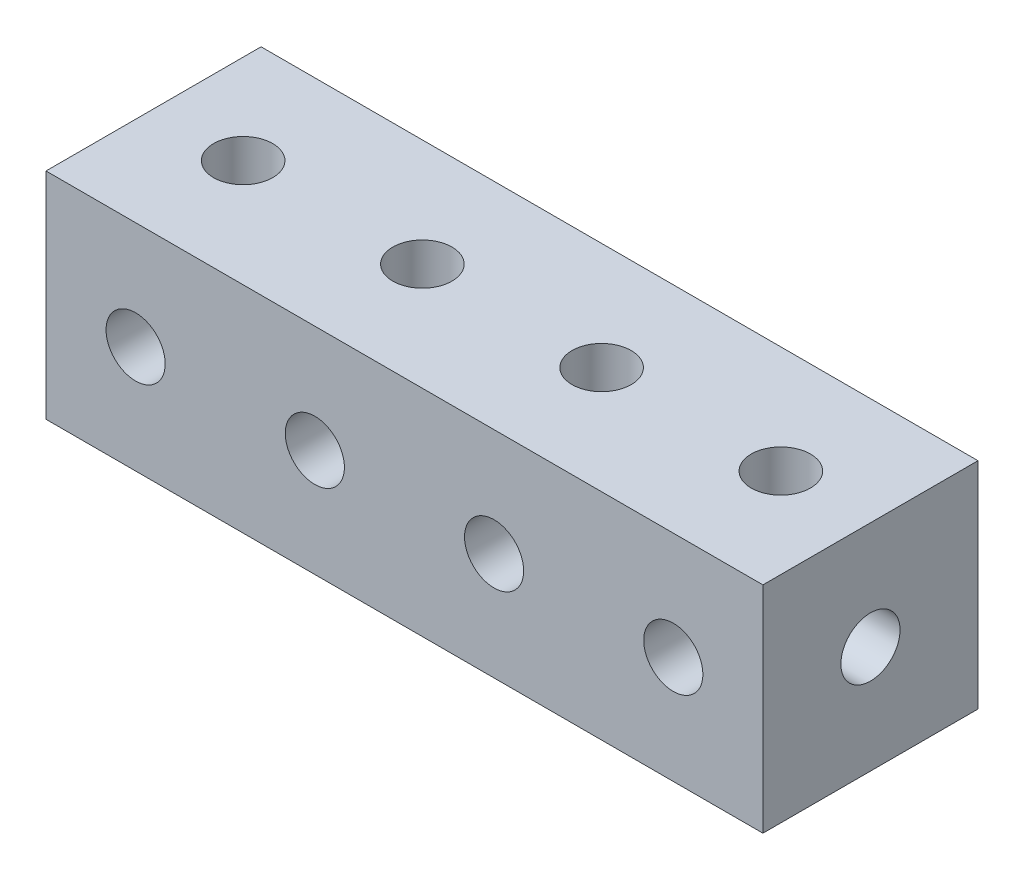
SolidWorks part; units mm, degrees
ref_plane "Plan de face" through (0, 0, 0) normal (0, 0, 1) x (1, 0, 0)
ref_plane "Plan de dessus" through (0, 0, 0) normal (0, 1, 0) x (1, 0, 0)
ref_plane "Plan de droite" through (0, 0, 0) normal (1, 0, 0) x (0, 0, -1)
sketch "Esquisse1" plane through (0, 0, 0) normal (1, 0, 0) x (0, 0, -1)
  line L1 (0, 0) -> (12, 0)
  line L2 (0, 0) -> (0, 12)
  line L3 (0, 12) -> (12, 12)
  line L4 (12, 0) -> (12, 12)
  dimension "D1" = 12
extrude "Boss.-Extru.1" add sketch "Esquisse1" along normal blind 40
sketch "Esquisse2" plane through (0, 12, 0) normal (0, 1, 0) x (1, 0, 0)
  line L0 (0, 6) -> (40, 6) construction
  line L1 (0, 12) -> (0, 0) construction
  line L2 (40, 12) -> (40, 0) construction
  circle A0 centre (5, 6) radius 1.65
  circle A1 centre (15, 6) radius 1.65
  circle A2 centre (25, 6) radius 1.65
  circle A3 centre (35, 6) radius 1.65
  dimension "D4" = 3.3
  dimension "D1" = 5
  dimension "D2" = 10
  dimension "D3" = 10
  dimension "D5" = 10
extrude "Enlèv. mat.-Extru.1" cut sketch "Esquisse2" against normal through all
sketch "Esquisse3" plane through (0, 0, 0) normal (0, 0, 1) x (1, 0, 0)
  line L0 (0, 6) -> (40, 6) construction
  line L1 (0, 12) -> (0, 0) construction
  line L2 (40, 12) -> (40, 0) construction
  circle A0 centre (5, 6) radius 1.65
  circle A1 centre (15, 6) radius 1.65
  circle A2 centre (25, 6) radius 1.65
  circle A3 centre (35, 6) radius 1.65
  dimension "D4" = 3.3
  dimension "D1" = 5
  dimension "D2" = 10
  dimension "D3" = 10
  dimension "D5" = 10
extrude "Enlèv. mat.-Extru.2" cut sketch "Esquisse3" against normal blind 40
sketch "Esquisse4" plane through (40, 0, 0) normal (1, 0, 0) x (0, 0, -1)
  line L0 (12, 12) -> (0, 0) construction
  circle A0 centre (6, 6) radius 1.65
  point P6 (6, 6)
  dimension "D1" = 3.3
extrude "Enlèv. mat.-Extru.3" cut sketch "Esquisse4" against normal blind 40
